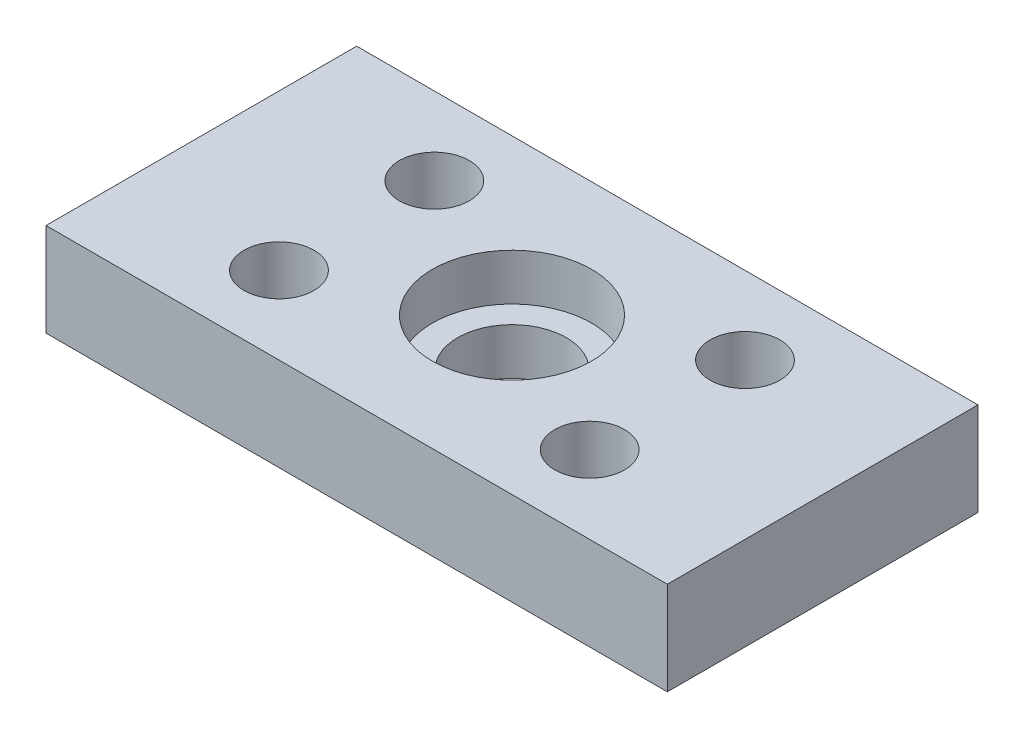
SolidWorks part; units mm, degrees
ref_plane "Спереди" through (0, 0, 0) normal (0, 0, 1) x (1, 0, 0)
ref_plane "Сверху" through (0, 0, 0) normal (0, 1, 0) x (1, 0, 0)
ref_plane "Справа" through (0, 0, 0) normal (1, 0, 0) x (0, 0, -1)
sketch "Эскиз2" plane through (0, 0, 0) normal (0, 1, 0) x (1, 0, 0)
  line L1 (-60, 10) -> (60, 10)
  line L2 (-60, 10) -> (-60, -10)
  line L3 (-60, -10) -> (60, -10)
  line L4 (60, 10) -> (60, -10)
  line L5 (-60, 10) -> (60, -10) construction
  line L6 (-60, -10) -> (60, 10) construction
  circle A0 centre (-50, 5) radius 2.25
  circle A1 centre (-30, 5) radius 2.25
  circle A2 centre (-10, 5) radius 2.25
  circle A3 centre (10, 5) radius 2.25 construction
  circle A4 centre (30, 5) radius 2.25
  circle A5 centre (50, 5) radius 2.25 construction
  circle A6 centre (-30, -5) radius 2.25
  circle A7 centre (-10, -5) radius 2.25 construction
  circle A8 centre (10, -5) radius 2.25
  circle A9 centre (30, -5) radius 2.25 construction
  circle A10 centre (50, -5) radius 2.25
  circle A11 centre (-50, -5) radius 2.25
  point P0 (0, 0)
  dimension "D3" = 4.5
  dimension "D1" = 20
  dimension "D2" = 120
  dimension "D4" = 5
  dimension "D5" = 10
  dimension "D9" = 5
  dimension "D8" = 40
  dimension "D6" = 6
  dimension "D7" = 2
extrude "Бобышка-Вытянуть1" add sketch "Эскиз2" along normal blind 6
sketch "Эскиз3" plane through (0, 6, 0) normal (0, 1, 0) x (1, 0, 0)
  line L0 (60, 10) -> (-60, 10) construction
  line L1 (-20, 10) -> (60, 10)
  line L2 (-20, 10) -> (-20, -10)
  line L3 (-20, -10) -> (60, -10)
  line L4 (60, 10) -> (60, -10)
  circle A0 centre (-30, -5) radius 2.25 construction
  dimension "D1" = 10
extrude "Вырез-Вытянуть1" cut sketch "Эскиз3" against normal through all
sketch "Эскиз4" plane through (0, 6, 0) normal (0, 1, 0) x (1, 0, 0)
  line L0 (-30, 5) -> (-50, -5) construction
  circle A0 centre (-40, 0) radius 5.125
  dimension "D1" = 10.25
extrude "Вырез-Вытянуть2" cut sketch "Эскиз4" against normal offset from surface (3 mm away) 3 up to face at (-40, 0, 0)
sketch "Эскиз5" plane through (0, 3, 0) normal (0, 1, 0) x (1, 0, 0)
  circle A0 centre (-40, 0) radius 3.5
  dimension "D1" = 7
extrude "Вырез-Вытянуть3" cut sketch "Эскиз5" against normal through all
equation "\"print_offset\"= 0.5"
equation "\"tape_width\"=51"
equation "\"tape_thikness\"=5"
equation "\"tape_distance\"=5"
equation "\"screw_d\"=3"
equation "\"screw_hh_d\"=5.3"
equation "\"nut_d\"=5.5"
equation "\"nut_h\"=2.5"
equation "\"sitting_screws\"=30"
equation "\"mount_size\"=42"
equation "\"hip_to_tube\" = 65"
equation "\"back_to_tube\"= 60"
equation "\"tube_d\"= 16"
equation "\"bearing_d1\"= 20"
equation "\"bearing_d2\"= 42"
equation "\"bearing_h\"= 12"
equation "\"tube_A\"= 250"
equation "\"tube_B\"= 384"
equation "\"tube_C\"= 300"
equation "\"tube_thikness\"=1"
equation "\"tube_bend_radius\"= 80"
equation "\"plate_a\"= 20"
equation "\"plate_b\"= 120"
equation "\"plate_holes\"= 5"
equation "\"plate_holes_a\"= ( 2.5 + 7.5 ) / 2"
equation "\"plate_holes_b\"= ( 7.5 + 12.5 ) / 2"
equation "\"plate_holes_step\"= 40"
equation "\"D1@Эскиз2\"=\"plate_a\""
equation "\"D2@Эскиз2\"=\"plate_b\""
equation "\"D4@Эскиз2\"=\"plate_holes\""
equation "\"D9@Эскиз2\"=\"D4@Эскиз2\""
equation "\"D5@Эскиз2\"=\"plate_holes_b\""
equation "\"D8@Эскиз2\"=\"plate_holes_step\""
equation "\"big_bearing_d1\"= 19.9"
equation "\"big_bearing_d2\"= 42"
equation "\"big_bearing_h\"= 11.9"
equation "\"small_bearing_d1\"= 2.9"
equation "\"small_bearing_d2\"= 10"
equation "\"small_bearing_h\"= 4"
equation "\"small_bearing_distance\"= 2"
equation "\"D1@Эскиз4\"=\"small_bearing_d2\"+\"print_offset\"/2"
equation "\"D1@Вырез-Вытянуть2\"=(\"tube_d\"-\"small_bearing_distance\"-\"small_bearing_h\"*2)/2"
